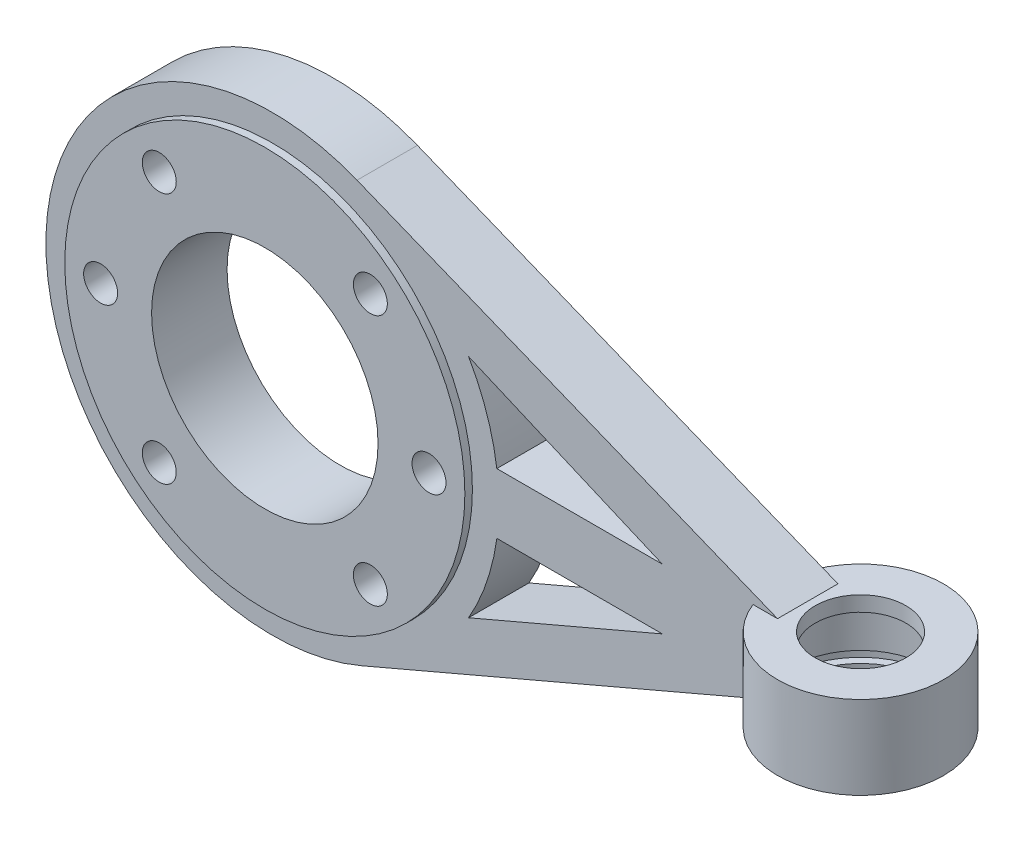
SolidWorks part; units mm, degrees
ref_plane "前视基准面" through (0, 0, 0) normal (0, 0, 1) x (1, 0, 0)
ref_plane "上视基准面" through (0, 0, 0) normal (0, 1, 0) x (1, 0, 0)
ref_plane "右视基准面" through (0, 0, 0) normal (1, 0, 0) x (0, 0, -1)
other "Configuration Table"
sketch "草图1" plane through (0, 0, 0) normal (0, 0, 1) x (1, 0, 0)
  circle A0 centre (0, 0) radius 30
  dimension "D1" = 60
extrude "凸台-拉伸1" add sketch "草图1" along normal blind 3
sketch "草图2" plane through (0, 0, 3) normal (0, 0, 1) x (1, 0, 0)
  line L0 (0, 0) -> (150.9371, 0) construction
  line L1 (73.9156, 22.7173) -> (73.9156, -21.6499) construction
  line L3 (62.9156, 5.375) -> (73.9156, 5.375)
  line L4 (62.9156, 5.375) -> (62.9156, -5.625)
  line L8 (62.9156, -5.625) -> (73.9156, -5.625)
  line L9 (73.9156, 5.375) -> (73.9156, -5.625)
  dimension "D2" = 11
  dimension "D1" = 73.9156
  dimension "D3" = 5.375
  dimension "D4" = 11
revolve "旋转1" add sketch "草图2" angle 360 about L1
sketch "草图3" plane through (0, 0, 3) normal (0, 0, 1) x (1, 0, 0)
  line L0 (11.2147, 27.825) -> (66.9156, 5.375)
  line L1 (11.801, -27.5814) -> (66.9156, -4)
  line L2 (73.9156, -5.625) -> (73.9156, 5.375) construction
  line L4 (66.9156, 5.375) -> (66.9156, -4)
  circle A1 centre (0, 0) radius 30
  arc A2 (11.2147, 27.825) -> (11.801, -27.5814) centre (0, 0) ccw
  dimension "D2" = 7
  dimension "D3" = 5.375
  dimension "D4" = 4
  dimension "D1" = 0
extrude "凸台-拉伸2" add sketch "草图3" along normal mid plane 8
sketch "草图4" plane through (0, -5.625, 0) normal (0, -1, 0) x (1, 0, 0)
  circle A0 centre (73.9156, 3) radius 6
  dimension "D1" = 12
extrude "切除-拉伸1" cut sketch "草图4" against normal blind 25
sketch "草图5" plane through (0, -5.625, 0) normal (0, -1, 0) x (1, 0, 0)
  circle A0 centre (73.9156, 3) radius 9
  dimension "D1" = 18
extrude "切除-拉伸2" cut sketch "草图5" against normal offset from surface (9 mm away) 2 up to face at (67.9156, 5.375, 3)
sketch "草图6" plane through (0, 3.375, 0) normal (0, -1, 0) x (1, 0, 0)
  circle A0 centre (73.9156, 3) radius 10
  circle A1 centre (73.9156, 3) radius 9 construction
  circle A2 centre (73.9156, 3) radius 9 construction
  circle A3 centre (73.9156, 3) radius 9
  circle M1 centre (73.9156, 3) radius 9
  dimension "D1" = 1
extrude "切除-拉伸3" cut sketch "草图6" along normal blind 1.5 from offset 6.5 contours A0 M1 | A3
ref_plane "基准面1" through (0, 0, 3) normal (0, 0, -1) x (-1, 0, 0)
sketch "草图8" plane through (0, 0, 3) normal (0, 0, -1) x (-1, 0, 0)
  circle A0 centre (0, 0) radius 26.5
  dimension "D1" = 53
extrude "凸台-拉伸3" add sketch "草图8" along normal mid plane 10
sketch "草图7" plane through (0, 0, 7) normal (0, 0, 1) x (1, 0, 0)
  line L0 (25.9897, -14.9845) -> (51.6627, -4)
  line L1 (0, 0) -> (55.8434, 0) construction
  line L2 (11.801, -27.5814) -> (63.6687, -5.3892) construction
  line L4 (29.7321, -4) -> (51.6627, -4)
  line L5 (29.7321, 4) -> (51.6627, 4)
  line L6 (25.9897, 14.9845) -> (51.6627, 4)
  circle A0 centre (0, 0) radius 15
  arc A1 (25.9897, -14.9845) -> (29.7321, -4) centre (0, 0) ccw
  arc A2 (25.9897, 14.9845) -> (29.7321, 4) centre (0, 0) cw
  dimension "D1" = 30
  dimension "D3" = 30
  dimension "D2" = 6
  dimension "D4" = 4
extrude "切除-拉伸4" cut sketch "草图7" against normal through all both and the other way through all
fillet "圆角1" [suppressed] radius 2
sketch "草图10" plane through (0, 0, 8) normal (0, 0, 1) x (1, 0, 0)
  line L0 (-42.7659, 0) -> (30.817, 0) construction
  line L1 (0, 0) -> (27.9613, -33.3229) construction
  line L2 (0, 31.5638) -> (0, -40.9894) construction
  circle A0 centre (21.75, 0) radius 2.25
  circle A1 centre (13.9806, -16.6615) radius 2.25
  circle A2 centre (-21.75, 0) radius 2.25
  circle A3 centre (-13.9806, -16.6615) radius 2.25
  circle A4 centre (13.9806, 16.6615) radius 2.25
  circle A5 centre (-13.9806, 16.6615) radius 2.25
  point P12 (14.8404, -17.686)
  dimension "D2" = 4.5
  dimension "D3" = 4.5
  dimension "D1" = 50
  dimension "D4" = 21.75
  dimension "D5" = 21.75
extrude "切除-拉伸5" cut sketch "草图10" against normal blind 17
